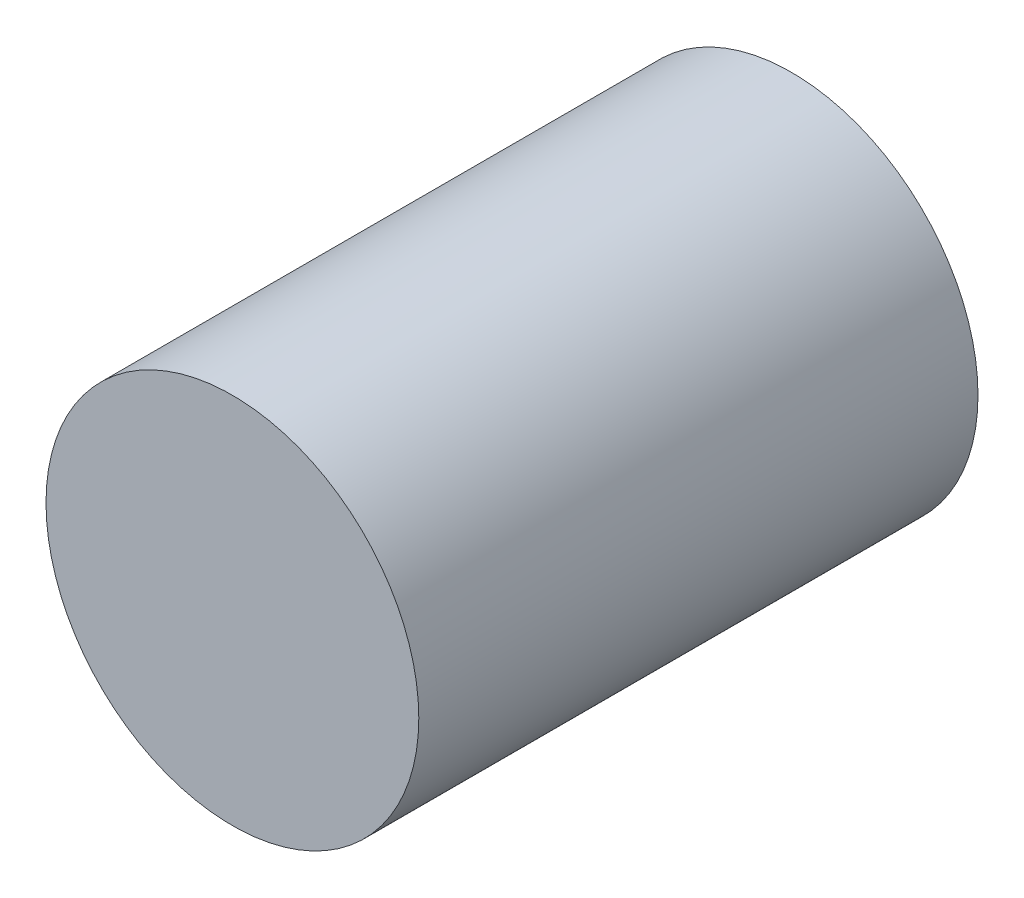
SolidWorks part; units mm, degrees
ref_plane "Plano frontal" through (0, 0, 0) normal (0, 0, 1) x (1, 0, 0)
ref_plane "Plano superior" through (0, 0, 0) normal (0, 1, 0) x (1, 0, 0)
ref_plane "Plano direito" through (0, 0, 0) normal (1, 0, 0) x (0, 0, -1)
sketch "Esboço1" plane through (0, 0, 0) normal (0, 0, 1) x (1, 0, 0)
  circle A0 centre (0, 0) radius 1
  dimension "D1" = 2
extrude "Ressalto-extrusão1" add sketch "Esboço1" along normal blind 3
